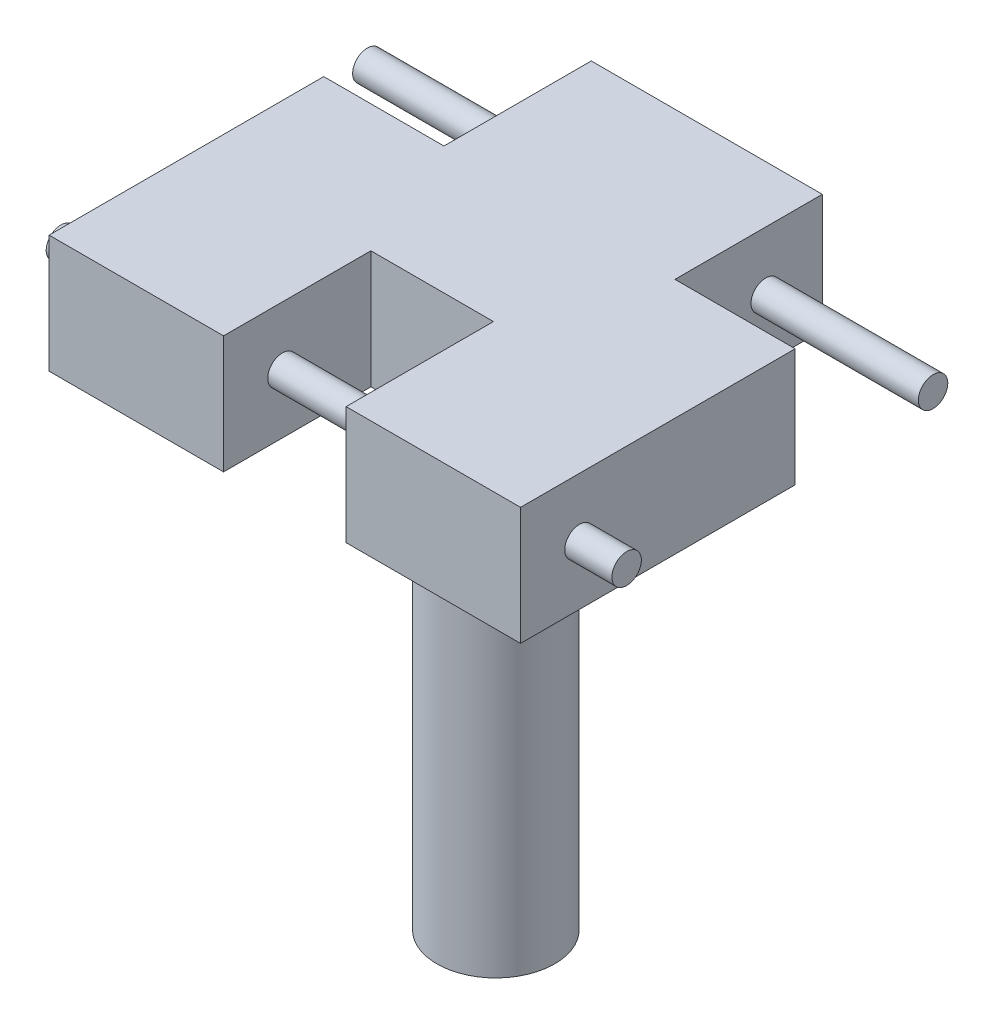
SolidWorks part; units mm, degrees
ref_plane "Front Plane" through (0, 0, 0) normal (0, 0, 1) x (1, 0, 0)
ref_plane "Top Plane" through (0, 0, 0) normal (0, 1, 0) x (1, 0, 0)
ref_plane "Right Plane" through (0, 0, 0) normal (1, 0, 0) x (0, 0, -1)
sketch "Sketch1" plane through (0, 0, 0) normal (0, 1, 0) x (1, 0, 0)
  line L0 (-6.223, 6.223) -> (6.223, 6.223)
  line L1 (6.223, 6.223) -> (6.223, -1.7145)
  line L2 (6.223, -1.7145) -> (12.7, -1.7145)
  line L3 (12.7, -1.7145) -> (12.7, -16.51)
  line L4 (12.7, -16.51) -> (3.302, -16.51)
  line L5 (3.302, -16.51) -> (3.302, -8.5725)
  line L6 (3.302, -8.5725) -> (-3.302, -8.5725)
  line L7 (-3.302, -8.5725) -> (-3.302, -16.51)
  line L8 (-3.302, -16.51) -> (-12.7, -16.51)
  line L9 (-12.7, -16.51) -> (-12.7, -1.7145)
  line L10 (-12.7, -1.7145) -> (-6.223, -1.7145)
  line L11 (-6.223, -1.7145) -> (-6.223, 6.223)
  dimension "D1" = 12.446
  dimension "D2" = 7.9375
  dimension "D3" = 6.858
  dimension "D4" = 9.398
  dimension "D5" = 7.9375
  dimension "D6" = 6.604
  dimension "D7" = 6.477
  dimension "D8" = 6.223
  dimension "D9" = 6.223
extrude "FingerBase" add sketch "Sketch1" along normal blind 6.35
sketch "Sketch2" plane through (12.7, 0, 0) normal (1, 0, 0) x (0, 0, -1)
  line L0 (-16.51, 6.35) -> (-1.7145, 6.35) construction
  line L1 (-16.51, 6.35) -> (-16.51, 0) construction
  line L2 (-1.7145, 6.35) -> (6.223, 6.35) construction
  line L3 (6.223, 6.35) -> (6.223, 0) construction
  circle A0 centre (-13.335, 3.175) radius 0.7937
  circle A1 centre (3.175, 3.175) radius 0.7937
  dimension "D1" = 1.5875
  dimension "D2" = 3.175
  dimension "D3" = 3.175
  dimension "D4" = 3.175
  dimension "D5" = 3.048
extrude "Boss-Extrude1" add sketch "Sketch2" along normal blind 2.54 and the other way blind 27.94
sketch "Sketch3" plane through (0, 0, 0) normal (0, -1, 0) x (1, 0, 0)
  line L1 (-3.302, 8.5725) -> (3.302, 8.5725) construction
  circle A0 centre (0, 5.1435) radius 3.175
  point P3 (0, 0)
  point P4 (0, 0)
  dimension "D1" = 6.35
  dimension "D2" = 3.429
extrude "Boss-Extrude2" add sketch "Sketch3" along normal blind 25.4
